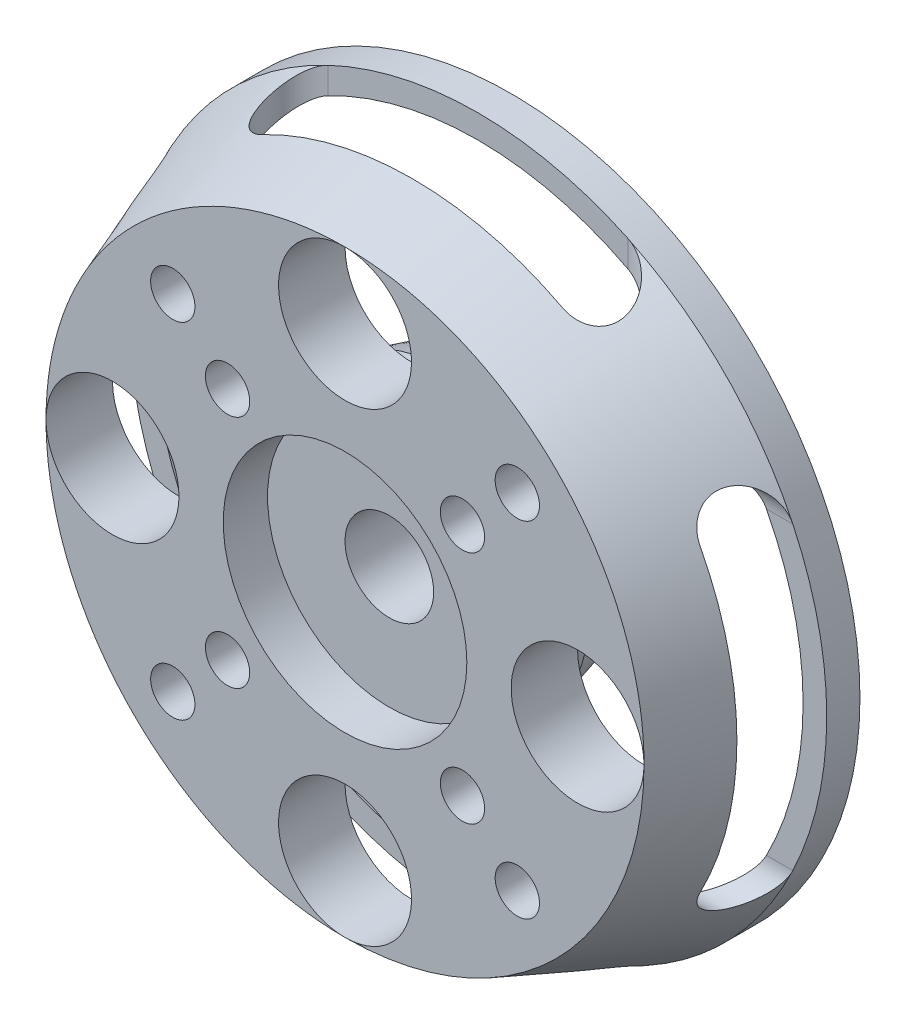
SolidWorks part; units mm, degrees
ref_plane "Front Plane" through (0, 0, 0) normal (0, 0, 1) x (1, 0, 0)
ref_plane "Top Plane" through (0, 0, 0) normal (0, 1, 0) x (1, 0, 0)
ref_plane "Right Plane" through (0, 0, 0) normal (1, 0, 0) x (0, 0, -1)
ref_axis "Z" through (0, 0, -15.75) along (0, 0, 1)
sketch "Sketch1" plane through (0, 0, 0) normal (0, 1, 0) x (1, 0, 0)
  line L0 (29.5, 15) -> (29.5, 12.3627)
  line L1 (29.5, 12.3627) -> (27.114, 6)
  line L2 (27.114, 6) -> (13, 6)
  line L3 (13, 6) -> (13, 9)
  line L4 (11.3923, 15) -> (4, 15)
  line L5 (4, 15) -> (4, 4)
  line L6 (11, 0) -> (27, 0)
  line L7 (27, 0) -> (31.5, 12)
  line L8 (31.5, 12) -> (31.5, 15)
  line L9 (31.5, 15) -> (29.5, 15)
  line L10 (0, -76.8889) -> (0, 67.6055) construction
  line L11 (11, 0) -> (11, 4)
  line L12 (11, 4) -> (4, 4)
  line L13 (4, 4) -> (4, 0) construction
  line L14 (4, 0) -> (11, 0) construction
  line L15 (11.3923, 15) -> (13, 9)
  line L16 (13, 15) -> (11.3923, 15) construction
  line L17 (13, 9) -> (13, 15) construction
  dimension "D1" = 8
  dimension "D2" = 15
  dimension "D3" = 2
  dimension "D4" = 3
  dimension "D5" = 2
  dimension "D6" = 63
  dimension "D7" = 6
  dimension "D8" = 9
  dimension "D9" = 54
  dimension "D10" = 22
  dimension "D11" = 4
  dimension "D12" = 15
  dimension "D13" = 3
revolve "Revolve1" add sketch "Sketch1" angle 360 about L10
ref_plane "Plane4" through (-31.5, 0, 0) normal (-1, 0, 0) x (0, 0, 1)
sketch "Sketch2" plane through (-31.5, 0, 0) normal (-1, 0, 0) x (0, 0, 1)
  line L0 (-9.05, -13.55) -> (-9.05, 13.55) construction
  line L1 (-12, -13.55) -> (-12, 13.55)
  line L2 (-6.1, -13.55) -> (-6.1, 13.55)
  line L3 (-15.75, 0) -> (0.75, 0) construction
  line L4 (-12.4387, -16.5) -> (-5.6613, -16.5) construction
  line L5 (-12.4387, 16.5) -> (-5.6613, 16.5) construction
  line L7 (-15, 29.5) -> (-15, -29.5) construction
  arc A0 (-12, -13.55) -> (-6.1, -13.55) centre (-9.05, -13.55) ccw
  arc A1 (-6.1, 13.55) -> (-12, 13.55) centre (-9.05, 13.55) ccw
  point P2 (-9.05, 0)
  dimension "D2" = 33
  dimension "D1" = 5.9
  dimension "D3" = 3
extrude "Cut-Extrude1" cut sketch "Sketch2" against normal blind 10
pattern_circular "CirPattern1" count 4 over 360 about axis through (0, 0, -15.75) along (0, 0, 1) of "Cut-Extrude1"
sketch "Sketch3" plane through (0, 0, 0) normal (0, 0, 1) x (1, 0, 0)
  line L0 (-21, 0) -> (0, 0) construction
  line L1 (0, 0) -> (-15.5563, 15.5563) construction
  circle A0 centre (-21, 0) radius 6
  circle A1 centre (0, 21) radius 6
  circle A2 centre (21, 0) radius 6
  circle A3 centre (0, -21) radius 6
  circle A4 centre (-15.5563, 15.5563) radius 2
  circle A5 centre (-10.6066, 10.6066) radius 2
  circle A6 centre (10.6066, 10.6066) radius 2
  circle A7 centre (15.5563, 15.5563) radius 2
  circle A8 centre (10.6066, -10.6066) radius 2
  circle A9 centre (15.5563, -15.5563) radius 2
  circle A10 centre (-10.6066, -10.6066) radius 2
  circle A11 centre (-15.5563, -15.5563) radius 2
  point P13 (0, 0)
  point P31 (0, 0)
  dimension "D1" = 12
  dimension "D5" = 4
  dimension "D2" = 21
  dimension "D4" = 45
  dimension "D6" = 7
  dimension "D7" = 15
  dimension "D3" = 4
  dimension "D8" = 4
extrude "Cut-Extrude2" cut sketch "Sketch3" against normal through all
equation "\"RotorMainLength\"= 41'rotor body longest dimension"
equation "\"OverallLength\"= 65.8'The height of the whole motor, not counting shaft protrusions"
equation "\"RotorDiameter\"= 63'Overall rotor diameter"
equation "\"RotorTopCapHeight\"= 14'Rough measurement/eyeballed. Not super critical for this; most important dim is overall length"
equation "\"RotorLargeHoleDiameter\"= 17'ID measurement with calipers"
equation "\"RotorLargeHoleTangentSpacing\"= 19'tangent to tangent on the large holes. add one diameter to achieve the center distances"
equation "\"RotorLargeHoleCenterDistance\"= \"RotorLargeHoleTangentSpacing\" + \"RotorLargeHoleDiameter\"'Center to center spacing for large hole"
equation "\"RotorSmallHoleID\"= 8'ID measurement with calipers"
equation "\"RotorSmallHoleTangentSpacing\"= 37'Tangent to Tangent (rounded to the nearest integer, real measurement was like 0.03mm off)"
equation "\"RotorSmallHoleCenterDistance\"= \"RotorSmallHoleID\" + \"RotorSmallHoleTangentSpacing\"'Center to center spacing for small holes"
equation "\"ShaftDiameter\"= 8"
equation "\"RotorShaftTopCapDiameter\"= 18'the small circular extrusion at the top of the rotor"
equation "\"RotorShaftTopCapHeight\"= 2'Height of the small cylindircal extrusion at the top of the rotor"
equation "\"RotorBoltCircleFlatDiameter\"= 30'Diameter of the flat portion where the bolt circle is drilled in the rotor"
equation "\"RotorTaperedEdgeHeight\"= 7'approximate, vertical distance of the tapered/angled edge of the rotor"
equation "\"RotorBoltCircleCenterDistance\"= 23mm'rounded, hard to measure with calipers so assuming they aren't fucking insane and chose this"
equation "\"StatorTrayHeight\"= 3+6+6\t'Rough measurement/eyeballed. Not super critical. Take up clearance in airgap; maintain overall height"
equation "\"StatorBaseOD\" = 54.00\t\t'OD of the base of the stator where the bolt circle is"
equation "\"StatorBoltCircleInnerRadius\"= 15"
equation "\"StatorBoltCircleDistance\"= 7"
equation "\"D1@Sketch1\"=\"ShaftDiameter\""
equation "\"D2@Sketch1\"=\"StatorTrayHeight\""
equation "\"D6@Sketch1\"=\"RotorDiameter\""
equation "\"D7@Sketch3\" = \"StatorBoltCircleInnerRadius\""
equation "\"D6@Sketch3\" = \"StatorBoltCircleDistance\""
equation "\"D1@Sketch3\"=12"
equation "\"D9@Sketch1\" = \"StatorBaseOD\""
